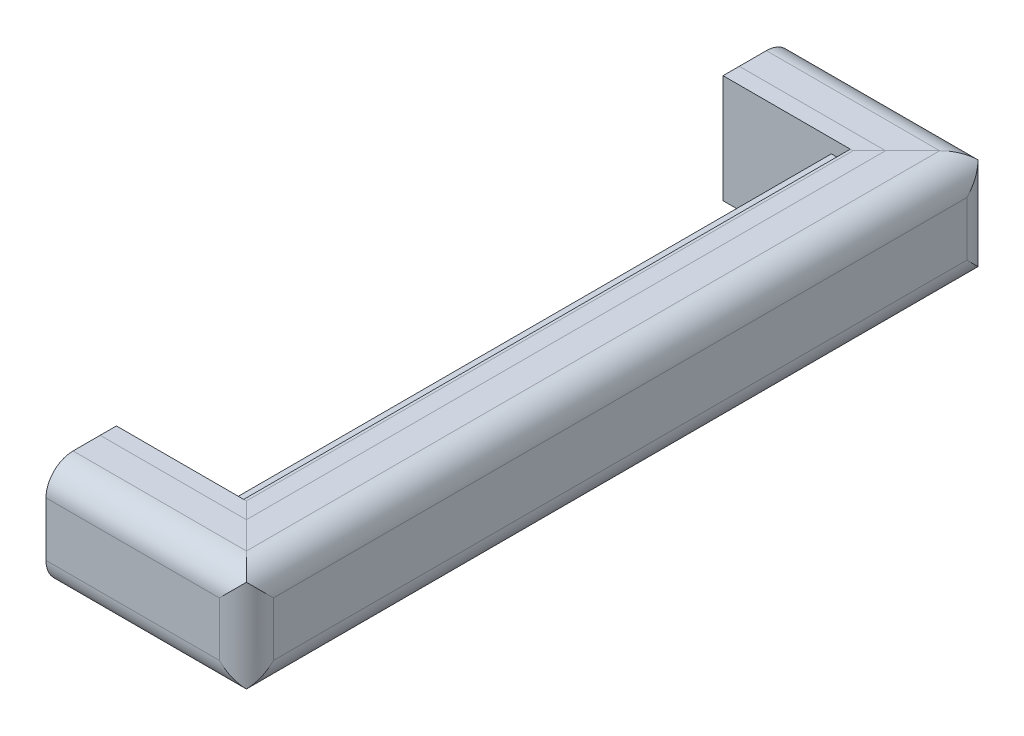
SolidWorks part; units mm, degrees
ref_plane "Front Plane" through (0, 0, 0) normal (0, 0, 1) x (1, 0, 0)
ref_plane "Top Plane" through (0, 0, 0) normal (0, 1, 0) x (1, 0, 0)
ref_plane "Right Plane" through (0, 0, 0) normal (1, 0, 0) x (0, 0, -1)
sketch "Sketch1" plane through (0, 0, 0) normal (1, 0, 0) x (0, 0, -1)
  line L0 (-355.6, 0) -> (0, 0) construction
  line L1 (-374.65, 63.5) -> (-355.6, 63.5)
  line L3 (-374.65, -63.5) -> (-355.6, -63.5)
  line L4 (-355.6, 63.5) -> (-355.6, -63.5)
  line L5 (-374.65, 63.5) -> (-406.4, 63.5)
  line L6 (-438.15, 31.75) -> (-438.15, -31.75)
  line L7 (-406.4, -63.5) -> (-374.65, -63.5)
  arc A0 (-406.4, 63.5) -> (-438.15, 31.75) centre (-406.4, 31.75) ccw
  arc A1 (-438.15, -31.75) -> (-406.4, -63.5) centre (-406.4, -31.75) ccw
  dimension "D4" = 31.75
  dimension "D1" = 355.6
  dimension "D2" = 127
  dimension "D3" = 19.05
  dimension "D5" = 50.8
sketch "Sketch2" plane through (0, 0, 0) normal (0, 1, 0) x (1, 0, 0)
  line L0 (0, -355.6) -> (152.4, -355.6)
  line L1 (152.4, -355.6) -> (152.4, 355.6)
  line L2 (152.4, 355.6) -> (0, 355.6)
  line L3 (0, 0) -> (152.4, 0) construction
  dimension "D1" = 152.4
sweep "Sweep1" add profiles "Sketch1" path "Sketch2"
sketch "Sketch3" plane through (0, 0, 0) normal (0, 1, 0) x (1, 0, 0)
  line L0 (203.2, -438.15) -> (234.95, -438.15)
  line L1 (234.95, -438.15) -> (234.95, -406.4)
  line L2 (234.95, 406.4) -> (234.95, 438.15)
  line L3 (234.95, 438.15) -> (203.2, 438.15)
  circle A0 centre (203.2, -406.4) radius 31.75
  circle A1 centre (203.2, 406.4) radius 31.75
extrude "Cut-Extrude1" cut sketch "Sketch3" against normal through all both and the other way through all contours A0 L0 L1 | A1 L2 L3
sketch "Sketch4" plane through (0, 0, 355.6) normal (0, 0, -1) x (-1, 0, 0)
  line L1 (-152.4, 63.5) -> (-149.225, 63.5)
  line L2 (-152.4, 63.5) -> (-152.4, 44.45)
  line L3 (-152.4, 44.45) -> (-149.225, 44.45)
  line L4 (-149.225, 63.5) -> (-149.225, 44.45)
  line L5 (-149.225, 47.625) -> (-127, 47.625)
  line L6 (-149.225, 47.625) -> (-149.225, 44.45)
  line L7 (-149.225, 44.45) -> (-127, 44.45)
  line L8 (-127, 47.625) -> (-127, 44.45)
  line M9 (0, 63.5) -> (-152.4, 63.5)
  line M10 (-152.4, 63.5) -> (-152.4, -63.5)
  dimension "D1" = 3.175
  dimension "D2" = 19.05
  dimension "D3" = 25.4
extrude "Boss-Extrude1" add sketch "Sketch4" along normal up to surface (711.2 mm away) separate body contours L4 L3 M9 M10 | L8 L5 L4 L7 up to face at (76.2, 0, -355.6)
